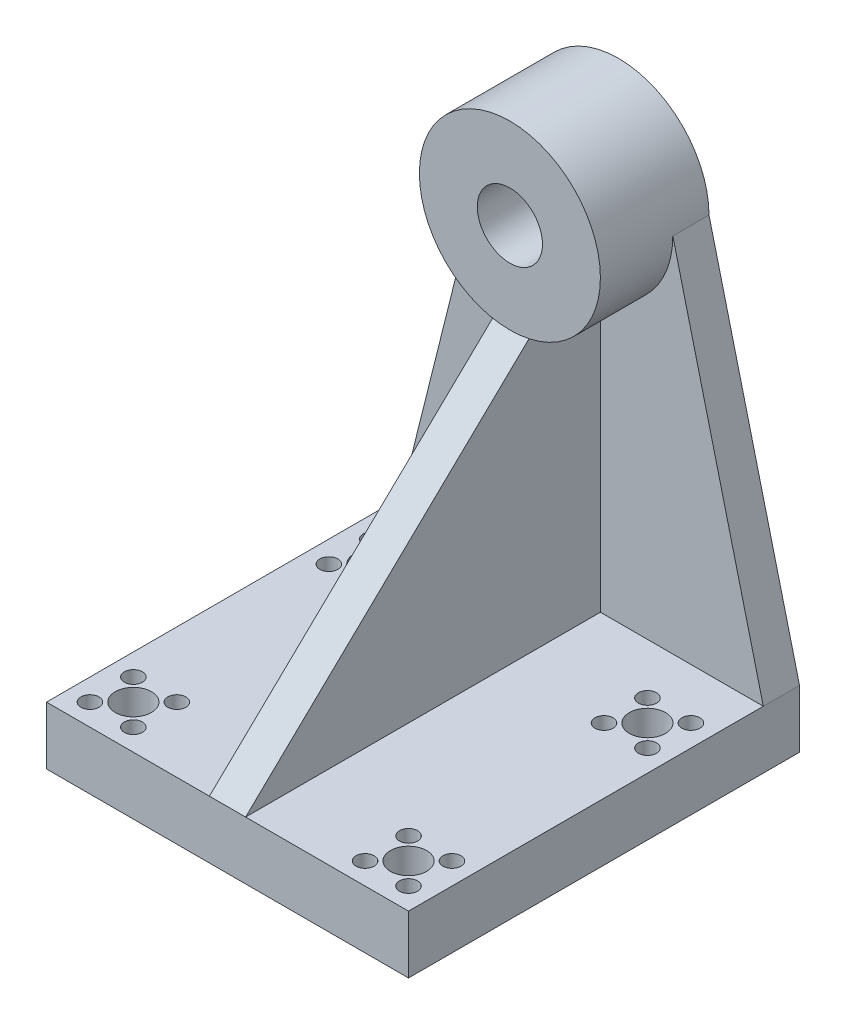
SolidWorks part; units mm, degrees
ref_plane "Front Plane" through (0, 0, 0) normal (0, 0, 1) x (1, 0, 0)
ref_plane "Top Plane" through (0, 0, 0) normal (0, 1, 0) x (1, 0, 0)
ref_plane "Right Plane" through (0, 0, 0) normal (1, 0, 0) x (0, 0, -1)
sketch "Sketch1" plane through (0, 0, 0) normal (0, 0, 1) x (1, 0, 0)
  circle A0 centre (0, 0) radius 22.5
  circle A1 centre (0, 0) radius 62.5
  dimension "D1" = 45
  dimension "D2" = 125
extrude "Boss-Extrude1" add sketch "Sketch1" along normal blind 75
sketch "Sketch3" plane through (0, 0, 0) normal (0, 0, -1) x (-1, 0, 0)
  line L0 (-62.5, 0) -> (-125, -250)
  line L1 (-125, -250) -> (125, -250)
  line L2 (125, -250) -> (62.5, 0)
  circle A0 centre (0, 0) radius 62.5 construction
  circle A2 centre (0, 0) radius 62.5
  arc A3 (-62.5, 0) -> (62.5, 0) centre (0, 0) ccw
  dimension "D1" = 250
  dimension "D2" = 250
  dimension "D3" = 250
  dimension "D4" = 0
extrude "Boss-Extrude2" add sketch "Sketch3" against normal blind 25
sketch "Sketch4" plane through (0, -250, 0) normal (0, -1, 0) x (1, 0, 0)
  line L0 (125, 0) -> (-125, 0)
  line L1 (125, 0) -> (125, 270)
  line L2 (-125, 0) -> (-125, 270)
  line L3 (125, 270) -> (-125, 270)
  dimension "D1" = 270
extrude "Boss-Extrude3" add sketch "Sketch4" along normal blind 40
sketch "Sketch5" plane through (0, -250, 0) normal (0, 1, 0) x (1, 0, 0)
  line L0 (0, -270) -> (0, -25)
  line L1 (125, -270) -> (-125, -270) construction
  line L2 (125, -25) -> (-125, -25) construction
sketch "Sketch6" plane through (0, 0, 0) normal (1, 0, 0) x (0, 0, -1)
  line L0 (-270, -250) -> (-75, -62.5)
rib "Rib5" sketch "Sketch6" sketch "Sketch6" thickness 25 extrusion direction parallel to sketch draft on no parameters "D1"=25
sketch "Sketch9" plane through (0, -290, 0) normal (0, -1, 0) x (1, 0, 0)
  line L0 (125, 270) -> (-125, 270) construction
  line L1 (-125, 270) -> (-125, 0) construction
  line L8 (95, 240) -> (-95, 240) construction
  circle A0 centre (-95, 240) radius 12.5
  circle A1 centre (-80, 255) radius 6.25
  circle A2 centre (-80, 225) radius 6.25
  circle A3 centre (-95, 240) radius 12.5
  circle A4 centre (-110, 225) radius 6.25
  circle A5 centre (-95, 240) radius 12.5
  circle A6 centre (-110, 255) radius 6.25
  circle A7 centre (-95, 240) radius 12.5
  circle A8 centre (110, 255) radius 6.25
  circle A9 centre (95, 240) radius 12.5
  circle A10 centre (110, 225) radius 6.25
  circle A11 centre (80, 225) radius 6.25
  circle A12 centre (80, 255) radius 6.25
  circle A13 centre (110, 90) radius 6.25
  circle A14 centre (95, 75) radius 12.5
  circle A15 centre (110, 60) radius 6.25
  circle A16 centre (80, 60) radius 6.25
  circle A17 centre (80, 90) radius 6.25
  circle A18 centre (-80, 90) radius 6.25
  circle A19 centre (-95, 75) radius 12.5
  circle A20 centre (-80, 60) radius 6.25
  circle A21 centre (-110, 60) radius 6.25
  circle A22 centre (-110, 90) radius 6.25
  dimension "D1" = 25
  dimension "D4" = 12.5
  dimension "D2" = 30
  dimension "D3" = 30
  dimension "D5" = 15
  dimension "D6" = 15
  dimension "D8" = 2
  dimension "D10" = 2
  dimension "D7" = 4
sketch "Sketch10" plane through (0, -250, 0) normal (0, 1, 0) x (1, 0, 0)
  line L0 (-95, -75) -> (-95, -240) construction
  line L1 (-95, -240) -> (95, -240) construction
  line L2 (95, -240) -> (95, -75) construction
  line L3 (95, -75) -> (-95, -75) construction
extrude "Cut-Extrude4" cut sketch "Sketch9" against normal blind 40 contours A4 | A6 | A14 | A0 | A1 | A2 | A10 | A9 | A8 | A12 | A11 | A13 | A15 | A16 | A17 | A20 | A18 | A22 | A21 | A19
